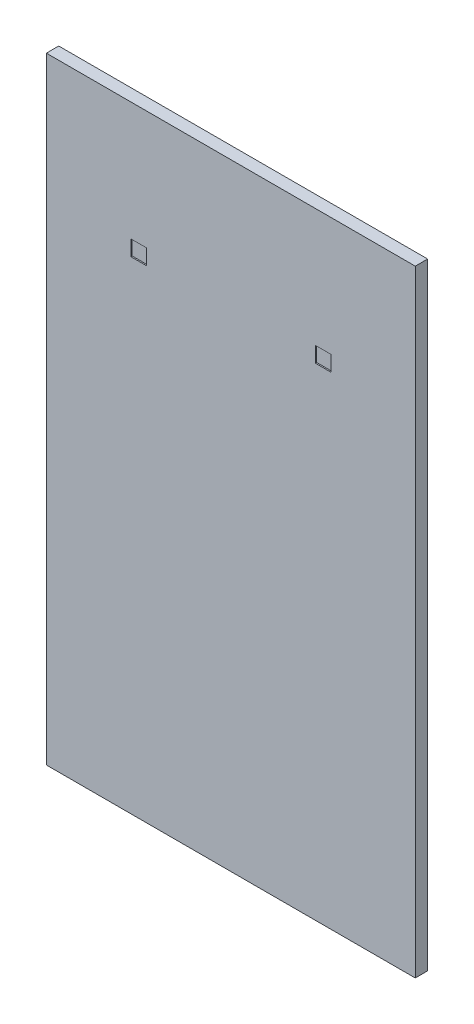
SolidWorks part; units mm, degrees
ref_plane "Front Plane" through (0, 0, 0) normal (0, 0, 1) x (1, 0, 0)
ref_plane "Top Plane" through (0, 0, 0) normal (0, 1, 0) x (1, 0, 0)
ref_plane "Right Plane" through (0, 0, 0) normal (1, 0, 0) x (0, 0, -1)
sketch "Sketch1" plane through (0, 0, 0) normal (0, 0, 1) x (1, 0, 0)
  line L1 (298, -498) -> (-298, -498)
  line L2 (298, -498) -> (298, 498)
  line L3 (298, 498) -> (-298, 498)
  line L4 (-298, -498) -> (-298, 498)
  line L5 (298, -498) -> (-298, 498) construction
  line L6 (298, 498) -> (-298, -498) construction
  point P0 (0, 0)
  dimension "D1" = 596
  dimension "D2" = 996
extrude "Boss-Extrude1" add sketch "Sketch1" along normal blind 20
sketch "Sketch2" plane through (0, 0, 20) normal (0, 0, 1) x (1, 0, 0)
  line L0 (-298, 294) -> (298, 294) construction
  line L1 (-298, 498) -> (-298, -498) construction
  line L2 (298, -498) -> (298, 498) construction
  line L3 (0, 498) -> (0, -519.4904) construction
  line L4 (298, 498) -> (-298, 498) construction
  line L5 (136.5, 281.5) -> (136.5, 306.5)
  line L6 (-136.5, 281.5) -> (-161.5, 281.5)
  line L7 (-136.5, 281.5) -> (-136.5, 306.5)
  line L8 (-136.5, 306.5) -> (-161.5, 306.5)
  line L9 (-161.5, 281.5) -> (-161.5, 306.5)
  line L10 (-136.5, 281.5) -> (-161.5, 306.5) construction
  line L11 (-136.5, 306.5) -> (-161.5, 281.5) construction
  line L12 (136.5, 281.5) -> (161.5, 281.5)
  line L13 (161.5, 281.5) -> (161.5, 306.5)
  line L14 (136.5, 306.5) -> (161.5, 306.5)
  point P11 (-149, 294)
  point P16 (0, 0)
  dimension "D1" = 204
  dimension "D2" = 25
  dimension "D3" = 25
  dimension "D4" = 136.5
extrude "Cut-Extrude1" cut sketch "Sketch2" against normal blind 2
